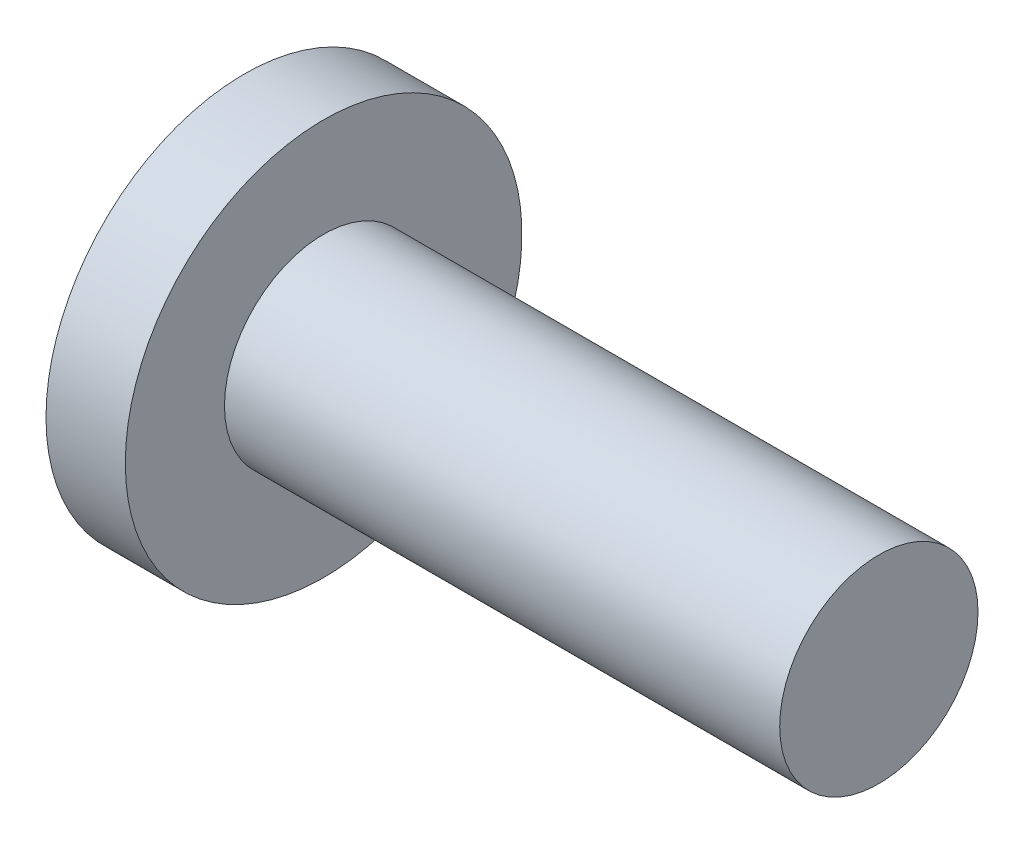
SolidWorks part; units mm, degrees
ref_plane "Plano frontal" through (0, 0, 0) normal (0, 0, 1) x (1, 0, 0)
ref_plane "Plano superior" through (0, 0, 0) normal (0, 1, 0) x (1, 0, 0)
ref_plane "Plano direito" through (0, 0, 0) normal (1, 0, 0) x (0, 0, -1)
sketch "Esboço1" plane through (0, 0, 0) normal (0, 0, 1) x (1, 0, 0)
  line L0 (-223.0763, 0) -> (10930.7401, 0) construction
  line L1 (0, 0) -> (0, 5)
  line L2 (0, 5) -> (2, 5)
  line L3 (2, 5) -> (2, 2.5)
  line L4 (2, 2.5) -> (16, 2.5)
  line L5 (16, 2.5) -> (16, 0)
  line L6 (0, 0) -> (16, 0)
  dimension "D1" = 10
  dimension "D2" = 2
  dimension "D3" = 16
  dimension "D4" = 5
revolve "Revolução1" add sketch "Esboço1" angle 360 about L0
scale "Escala1" scale about centroid uniform scaling yes scale factor 0.5
sketch "Croquis1" plane through (4.0455, 0, 0) normal (1, 0, 0) x (0, 0, -1)
  circle A0 centre (0, 0) radius 1.25
